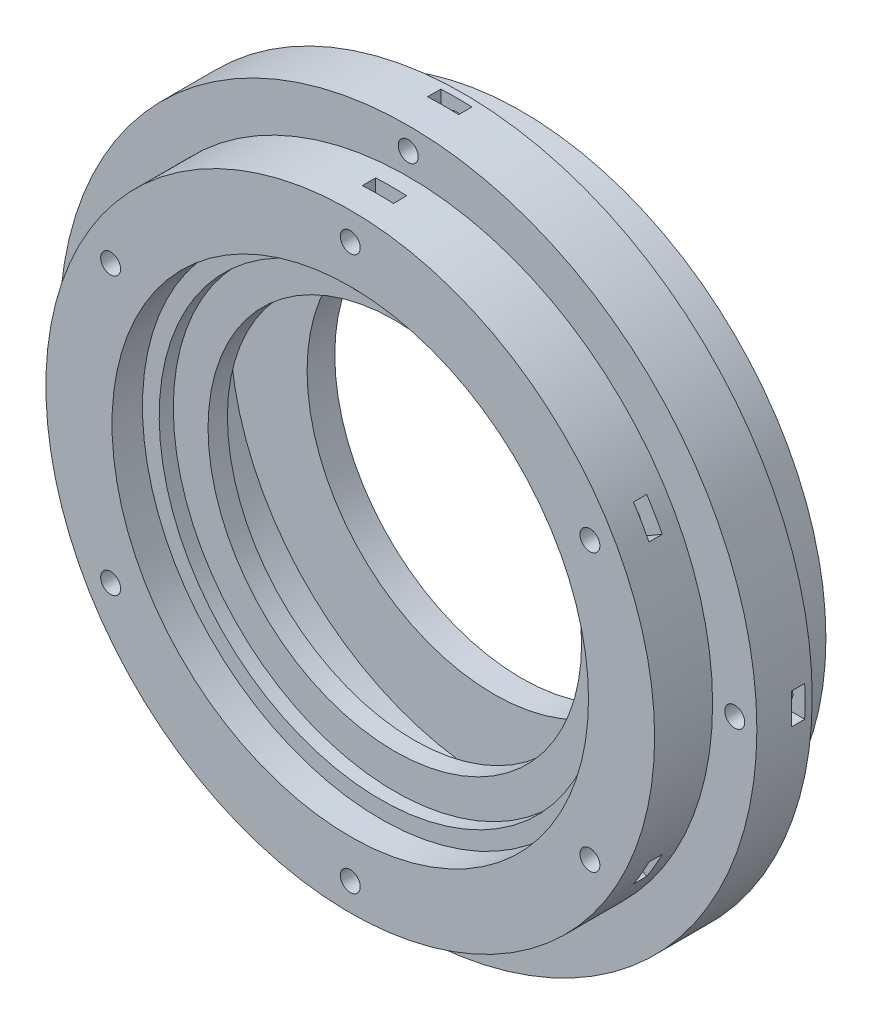
SolidWorks part; units mm, degrees
ref_plane "Front Plane" through (0, 0, 0) normal (0, 0, 1) x (1, 0, 0)
ref_plane "Top Plane" through (0, 0, 0) normal (0, 1, 0) x (1, 0, 0)
ref_plane "Right Plane" through (0, 0, 0) normal (1, 0, 0) x (0, 0, -1)
sketch "Sketch1" plane through (0, 0, 0) normal (0, 1, 0) x (1, 0, 0)
  line L0 (0, -39.8518) -> (0, 55.2469) construction
  line L1 (-67.4266, 0) -> (79.5088, 0) construction
  line L2 (43.05, 0) -> (43.05, 5.5)
  line L3 (43.05, 5.5) -> (40.025, 5.5)
  line L4 (40.025, 5.5) -> (40.025, 8.05)
  line L5 (40.025, 8.05) -> (33.75, 8.05)
  line L6 (33.75, 8.05) -> (33.75, 11.55)
  line L7 (33.75, 11.55) -> (47.68, 11.55)
  line L8 (47.68, 11.55) -> (47.68, 25.95)
  line L9 (47.68, 25.95) -> (33.75, 25.95)
  line L10 (33.75, 25.95) -> (33.75, 30.95)
  line L11 (33.75, 30.95) -> (44.2, 30.95)
  line L12 (55, 30.95) -> (55, 20.475)
  line L13 (55, 0) -> (43.05, 0)
  line L14 (50, -7.9548) -> (50, 44.3819) construction
  line L15 (53.5, 30.95) -> (53.5, 23.95)
  line L16 (53.5, 23.95) -> (50.35, 23.95)
  line L17 (50.35, 23.95) -> (50.35, 28.95)
  line L18 (50.35, 28.95) -> (44.2, 28.95)
  line L19 (44.2, 28.95) -> (44.2, 30.95)
  line L20 (53.5, 30.95) -> (55, 30.95)
  line L21 (-7.0531, 15.475) -> (69.523, 15.475) construction
  line L22 (55, 10.475) -> (63, 10.475)
  line L23 (63, 10.475) -> (63, 20.475)
  line L24 (63, 20.475) -> (55, 20.475)
  line L25 (55, 10.475) -> (55, 0)
  dimension "D1" = 47.68
  dimension "D2" = 14.4
  dimension "D3" = 3.5
  dimension "D4" = 5
  dimension "D5" = 2.55
  dimension "D6" = 5.5
  dimension "D7" = 33.75
  dimension "D8" = 33.75
  dimension "D9" = 40.025
  dimension "D10" = 43.05
  dimension "D11" = 55
  dimension "D12" = 50
  dimension "D13" = 53.5
  dimension "D14" = 3.15
  dimension "D15" = 5
  dimension "D16" = 6.15
  dimension "D17" = 7
  dimension "D18" = 15.475
  dimension "D19" = 76.5761
  dimension "D20" = 8
  dimension "D21" = 10
  dimension "D22" = 5
revolve "Revolve1" add sketch "Sketch1" angle 360 about L0
sketch "Sketch2" plane through (0, 0, 0) normal (0, 0, 1) x (1, 0, 0)
  line L0 (0, 63.3521) -> (0, -60.1897) construction
  circle A0 centre (0, 50) radius 1.8
  circle A1 centre (43.3013, 25) radius 1.8
  circle A2 centre (43.3013, -25) radius 1.8
  circle A3 centre (0, -50) radius 1.8
  circle A4 centre (-43.3013, -25) radius 1.8
  circle A5 centre (-43.3013, 25) radius 1.8
  point P17 (0, 0)
  dimension "D1" = 3.6
  dimension "D2" = 50
  dimension "D3" = 6
extrude "Cut-Extrude1" cut sketch "Sketch2" against normal blind 10
ref_plane "Plane1" through (0, 0, -5) normal (0, 0, 1) x (1, 0, 0)
sketch "Sketch3" plane through (0, 0, -5) normal (0, 0, 1) x (1, 0, 0)
  line L0 (0, 65.4647) -> (0, -62.7269) construction
  line L1 (-2.8, 57.8914) -> (-2.8, 47.2)
  line L2 (-2.8, 47.2) -> (2.8, 47.2)
  line L3 (2.8, 47.2) -> (2.8, 57.8914)
  line L4 (2.8, 57.8914) -> (-2.8, 57.8914)
  line L5 (51.5355, 26.5208) -> (48.7355, 31.3706)
  line L6 (48.7355, 31.3706) -> (39.4764, 26.0249)
  line L7 (39.4764, 26.0249) -> (42.2764, 21.1751)
  line L8 (42.2764, 21.1751) -> (51.5355, 26.5208)
  line L9 (48.7355, -31.3706) -> (51.5355, -26.5208)
  line L10 (51.5355, -26.5208) -> (42.2764, -21.1751)
  line L11 (42.2764, -21.1751) -> (39.4764, -26.0249)
  line L12 (39.4764, -26.0249) -> (48.7355, -31.3706)
  line L13 (-2.8, -57.8914) -> (2.8, -57.8914)
  line L14 (2.8, -57.8914) -> (2.8, -47.2)
  line L15 (2.8, -47.2) -> (-2.8, -47.2)
  line L16 (-2.8, -47.2) -> (-2.8, -57.8914)
  line L17 (-51.5355, -26.5208) -> (-48.7355, -31.3706)
  line L18 (-48.7355, -31.3706) -> (-39.4764, -26.0249)
  line L19 (-39.4764, -26.0249) -> (-42.2764, -21.1751)
  line L20 (-42.2764, -21.1751) -> (-51.5355, -26.5208)
  line L21 (-48.7355, 31.3706) -> (-51.5355, 26.5208)
  line L22 (-51.5355, 26.5208) -> (-42.2764, 21.1751)
  line L23 (-42.2764, 21.1751) -> (-39.4764, 26.0249)
  line L24 (-39.4764, 26.0249) -> (-48.7355, 31.3706)
  circle A0 centre (0, 50) radius 1.8 construction
  point P31 (0, 0)
  dimension "D3" = 2.8
  dimension "D1" = 5.6
  dimension "D2" = 2.8
  dimension "D4" = 6
extrude "Cut-Extrude2" cut sketch "Sketch3" against normal blind 2.4
sketch "Sketch4" plane through (0, 0, -5.5) normal (0, 0, 1) x (1, 0, 0)
  line L0 (0, 77.2348) -> (0, -70.1284) construction
  line L1 (-2.45, 42.9802) -> (-2.45, 39.9499)
  line L2 (2.45, 42.9802) -> (2.45, 39.9499)
  circle A0 centre (0, 0) radius 40.025 construction
  circle A1 centre (0, 0) radius 43.05 construction
  arc A2 (2.45, 39.9499) -> (-2.45, 39.9499) centre (0, 0) ccw
  arc A3 (2.45, 42.9802) -> (-2.45, 42.9802) centre (0, 0) ccw
  point P11 (-2.45, 41.4651)
  dimension "D1" = 2.45
extrude "Boss-Extrude1" add sketch "Sketch4" along normal blind 2.5
sketch "Sketch5" plane through (0, 0, -10.475) normal (0, 0, 1) x (1, 0, 0)
  line L0 (0, 69.6791) -> (0, -69.6791) construction
  circle A0 centre (0, 59) radius 1.8
  circle A1 centre (59, 0) radius 1.8
  circle A2 centre (0, -59) radius 1.8
  circle A3 centre (-59, 0) radius 1.8
  point P14 (0, 0)
  dimension "D1" = 3.6
  dimension "D2" = 59
  dimension "D3" = 4
extrude "Cut-Extrude3" cut sketch "Sketch5" against normal through all
ref_plane "Plane2" through (0, 0, -16.775) normal (0, 0, 1) x (1, 0, 0)
sketch "Sketch6" plane through (0, 0, -16.775) normal (0, 0, 1) x (1, 0, 0)
  line L0 (0, 74.0645) -> (0, -72.5887) construction
  line L1 (-2.8, 66.3687) -> (-2.8, 56.2)
  line L2 (-2.8, 56.2) -> (2.8, 56.2)
  line L3 (-2.8, 66.3687) -> (2.8, 66.3687)
  line L4 (2.8, 66.3687) -> (2.8, 56.2)
  line L5 (66.3687, -2.8) -> (56.2, -2.8)
  line L6 (56.2, 2.8) -> (56.2, -2.8)
  line L7 (66.3687, 2.8) -> (56.2, 2.8)
  line L8 (66.3687, 2.8) -> (66.3687, -2.8)
  line L9 (-2.8, -66.3687) -> (-2.8, -56.2)
  line L10 (2.8, -56.2) -> (-2.8, -56.2)
  line L11 (2.8, -66.3687) -> (2.8, -56.2)
  line L12 (2.8, -66.3687) -> (-2.8, -66.3687)
  line L13 (-66.3687, 2.8) -> (-56.2, 2.8)
  line L14 (-56.2, -2.8) -> (-56.2, 2.8)
  line L15 (-66.3687, -2.8) -> (-56.2, -2.8)
  line L16 (-66.3687, -2.8) -> (-66.3687, 2.8)
  circle A0 centre (0, 59) radius 1.8 construction
  point P24 (0, 0)
  dimension "D1" = 5.6
  dimension "D2" = 2.8
  dimension "D3" = 2.8
  dimension "D4" = 4
extrude "Cut-Extrude4" cut sketch "Sketch6" against normal blind 2.4
